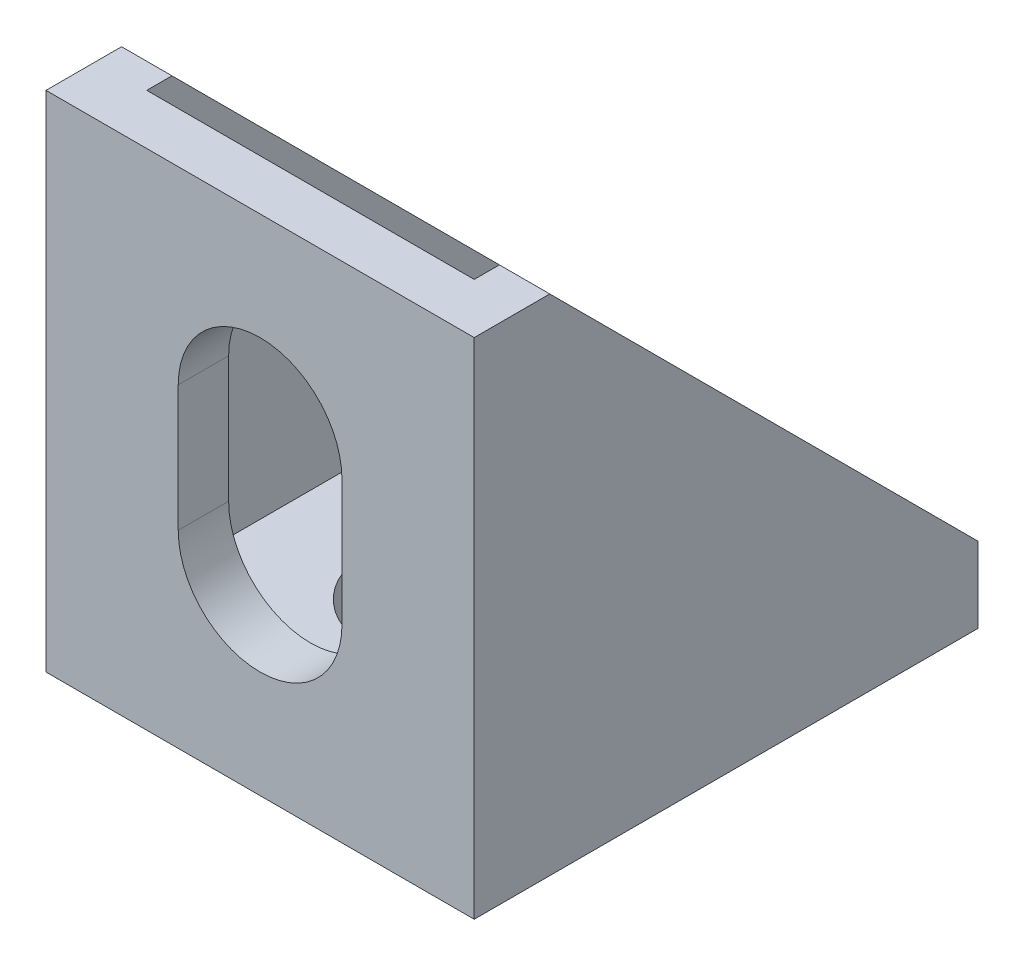
SolidWorks part; units mm, degrees
ref_plane "Front Plane" through (0, 0, 0) normal (0, 0, 1) x (1, 0, 0)
ref_plane "Top Plane" through (0, 0, 0) normal (0, 1, 0) x (1, 0, 0)
ref_plane "Right Plane" through (0, 0, 0) normal (1, 0, 0) x (0, 0, -1)
sketch "Sketch1" plane through (0, 0, 0) normal (1, 0, 0) x (0, 0, -1)
  line L0 (3, 20) -> (0, 20)
  line L1 (0, 20) -> (0, 0)
  line L2 (0, 0) -> (20, 0)
  line L3 (20, 0) -> (20, 3)
  line L4 (20, 3) -> (3, 20)
  dimension "D1" = 3
  dimension "D2" = 20
extrude "Body" add sketch "Sketch1" along normal mid plane 17
sketch "Sketch2" plane through (0, 0, -20) normal (0, 0, -1) x (-1, 0, 0)
  line L0 (-8.5, 3) -> (8.5, 3) construction
  line L1 (-6.5, 3) -> (6.5, 3)
  line L2 (-6.5, 3) -> (-6.5, 20)
  line L3 (-6.5, 20) -> (6.5, 20)
  line L4 (6.5, 3) -> (6.5, 20)
  line L5 (-8.5, 20) -> (8.5, 20) construction
  line L6 (8.5, 3) -> (8.5, 20) construction
  dimension "D1" = 2
  dimension "D2" = 2
extrude "Extusion" cut sketch "Sketch2" against normal offset from surface (18 mm away) 2 up to face at (0, 10, 0)
sketch "Sketch3" plane through (0, 0, -2) normal (0, 0, -1) x (-1, 0, 0)
  line L0 (0, 7.5) -> (0, 12.5) construction
  line L1 (-3.25, 7.5) -> (-3.25, 12.5)
  line L2 (3.25, 7.5) -> (3.25, 12.5)
  line L3 (-6.5, 20) -> (6.5, 20) construction
  line L4 (-8.5, 20) -> (-8.5, 0) construction
  line L5 (-8.5, 0) -> (8.5, 0) construction
  line L6 (8.5, 20) -> (8.5, 0) construction
  arc A0 (-3.25, 7.5) -> (3.25, 7.5) centre (0, 7.5) ccw
  arc A1 (3.25, 12.5) -> (-3.25, 12.5) centre (0, 12.5) ccw
  point P2 (0, 10)
  dimension "D1" = 6.5
  dimension "D2" = 5
  dimension "D3" = 10
extrude "Hole_A" cut sketch "Sketch3" against normal through all
sketch "Sketch4" plane through (0, 3, 0) normal (0, 1, 0) x (1, 0, 0)
  line L0 (0, 7.5) -> (0, 12.5) construction
  line L1 (-3.25, 7.5) -> (-3.25, 12.5)
  line L2 (3.25, 7.5) -> (3.25, 12.5)
  line L4 (6.5, 20) -> (-6.5, 20) construction
  arc A0 (-3.25, 7.5) -> (3.25, 7.5) centre (0, 7.5) ccw
  arc A1 (3.25, 12.5) -> (-3.25, 12.5) centre (0, 12.5) ccw
  point P3 (0, 10)
  dimension "D1" = 6.5
  dimension "D2" = 5
  dimension "D3" = 10
extrude "Hole_B" cut sketch "Sketch4" against normal blind 17
